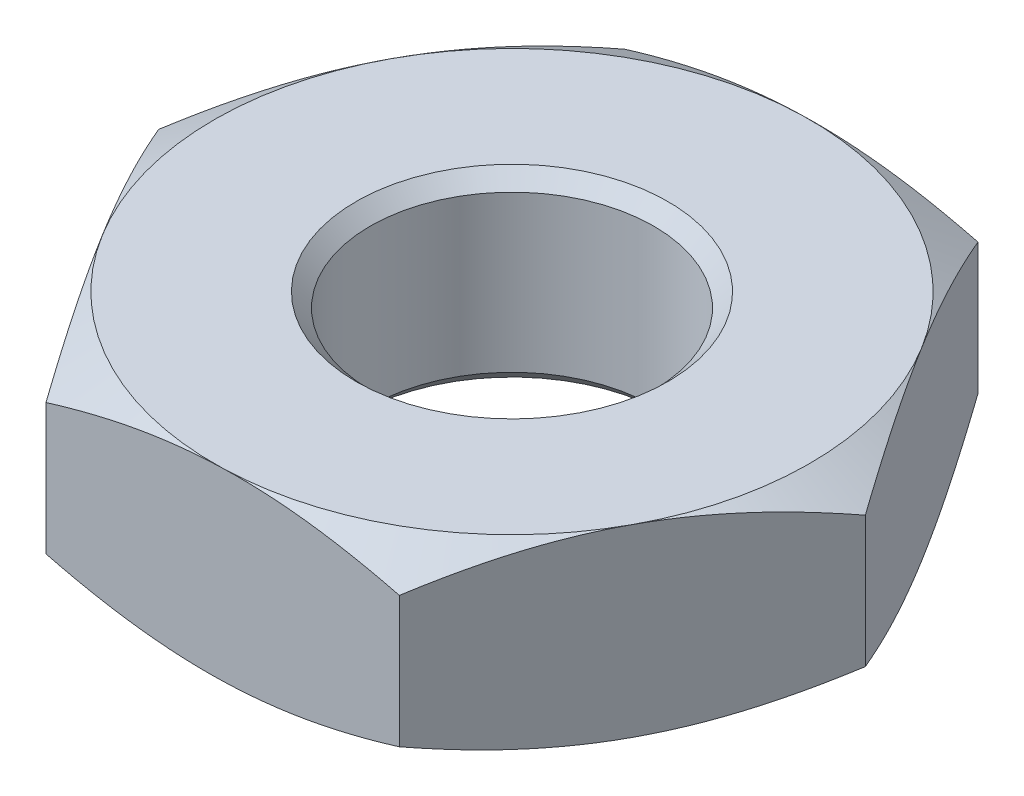
SolidWorks part; units mm, degrees
ref_plane "Front Plane" through (0, 0, 0) normal (0, 0, 1) x (1, 0, 0)
ref_plane "Top Plane" through (0, 0, 0) normal (0, 1, 0) x (1, 0, 0)
ref_plane "Right Plane" through (0, 0, 0) normal (1, 0, 0) x (0, 0, -1)
sketch "Sketch1" plane through (0, 0, 0) normal (0, 1, 0) x (1, 0, 0)
  line L1 (1.1532, 2.1331) -> (-1.2707, 2.0653)
  line L2 (-1.2707, 2.0653) -> (-2.4239, -0.0678)
  line L3 (-2.4239, -0.0678) -> (-1.1532, -2.1331)
  line L4 (-1.1532, -2.1331) -> (1.2707, -2.0653)
  line L5 (1.2707, -2.0653) -> (2.4239, 0.0678)
  line L6 (2.4239, 0.0678) -> (1.1532, 2.1331)
  circle A0 centre (0, 0) radius 2.1 construction
  circle A1 centre (0, 0) radius 1
  dimension "D1" = 2
  dimension "D2" = 4.2
extrude "Boss-Extrude1" add sketch "Sketch1" along normal blind 1.3
sketch "Sketch2" plane through (0, 1.3, 0) normal (0, 1, 0) x (1, 0, 0)
  line L0 (-1.2707, 2.0653) -> (-2.4239, -0.0678) construction
  circle A0 centre (0, 0) radius 2.1
extrude "Cut-Extrude1" cut sketch "Sketch2" against normal blind 177.8 draft 60 flip side to cut
sketch "Sketch3" plane through (0, 0, 0) normal (0, -1, 0) x (1, 0, 0)
  line L0 (-2.4239, 0.0678) -> (-1.1532, 2.1331) construction
  circle A0 centre (0, 0) radius 2.1
extrude "Cut-Extrude2" cut sketch "Sketch3" against normal blind 177.8 draft 60 flip side to cut
chamfer "Chamfer1" distance 0.1 angle 45 1 edges at (0, 1.3, 1)
chamfer "Chamfer2" distance 0.1 angle 45 1 edges at (0, 0, 1)
